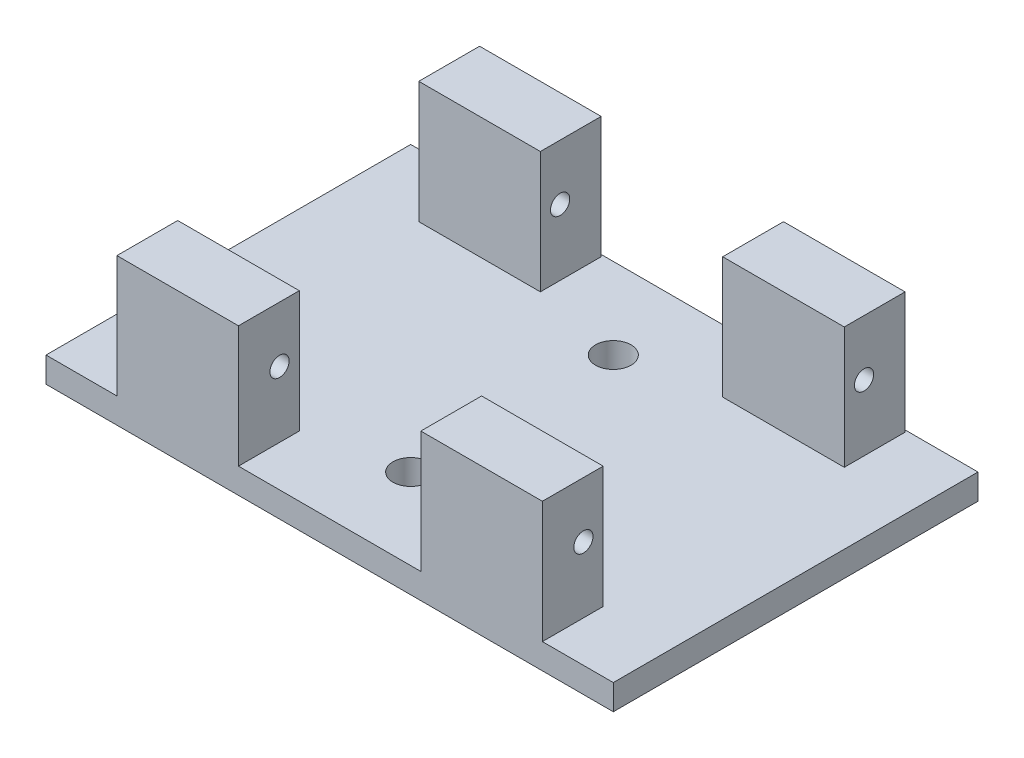
SolidWorks part; units mm, degrees
ref_plane "前视基准面" through (0, 0, 0) normal (0, 0, 1) x (1, 0, 0)
ref_plane "上视基准面" through (0, 0, 0) normal (0, 1, 0) x (1, 0, 0)
ref_plane "右视基准面" through (0, 0, 0) normal (1, 0, 0) x (0, 0, -1)
other "Configuration Table"
sketch "草图1" plane through (0, 0, 0) normal (0, 1, 0) x (1, 0, 0)
  line L1 (-28, 18) -> (28, 18)
  line L2 (-28, 18) -> (-28, -18)
  line L3 (-28, -18) -> (28, -18)
  line L4 (28, 18) -> (28, -18)
  line L5 (-28, 18) -> (28, -18) construction
  line L6 (-28, -18) -> (28, 18) construction
  point P0 (0, 0)
  dimension "D1" = 56
  dimension "D2" = 36
extrude "凸台-拉伸1" add sketch "草图1" along normal blind 2.5
sketch "草图2" plane through (0, 2.5, 0) normal (0, 1, 0) x (1, 0, 0)
  line L0 (-28, -18) -> (28, -18) construction
  line L1 (9, 17.8) -> (21, 17.8)
  line L2 (9, 17.8) -> (9, 11.8)
  line L3 (9, 11.8) -> (21, 11.8)
  line L4 (21, 17.8) -> (21, 11.8)
  line L5 (9, -12) -> (21, -12)
  line L6 (9, -12) -> (9, -18)
  line L7 (9, -18) -> (21, -18)
  line L8 (21, -12) -> (21, -18)
  line L9 (28, -18) -> (28, 18) construction
  dimension "D1" = 23.8
  dimension "D2" = 6
  dimension "D3" = 6
  dimension "D4" = 12
  dimension "D5" = 7
extrude "凸台-拉伸2" add sketch "草图2" along normal blind 12
sketch "草图3" plane through (21, 0, 0) normal (1, 0, 0) x (0, 0, -1)
  line L0 (-18, 2.5) -> (18, 2.5) construction
  line L1 (11.8, 2.5) -> (17.8, 2.5) construction
  line L2 (-12, 14.5) -> (-12, 2.5) construction
  line L3 (11.8, 14.5) -> (11.8, 2.5) construction
  circle A0 centre (-13.95, 9) radius 0.95
  circle A1 centre (13.75, 9) radius 0.95
  dimension "D1" = 6.5
  dimension "D2" = 6.5
  dimension "D3" = 1.95
  dimension "D4" = 1.95
  dimension "D5" = 1.9
  dimension "D6" = 1.9
extrude "切除-拉伸1" cut sketch "草图3" against normal through all
mirror "镜向1" about plane through (0, 0, 0) normal (1, 0, 0) of "切除-拉伸1", "凸台-拉伸2"
sketch "草图4" plane through (0, 2.5, 0) normal (0, 1, 0) x (1, 0, 0)
  circle A0 centre (0, -10) radius 1.75
  circle A1 centre (0, 10) radius 1.75
  dimension "D1" = 20
  dimension "D2" = 3.5
  dimension "D3" = 3.5
  dimension "D4" = 10
extrude "切除-拉伸2" cut sketch "草图4" against normal through all
